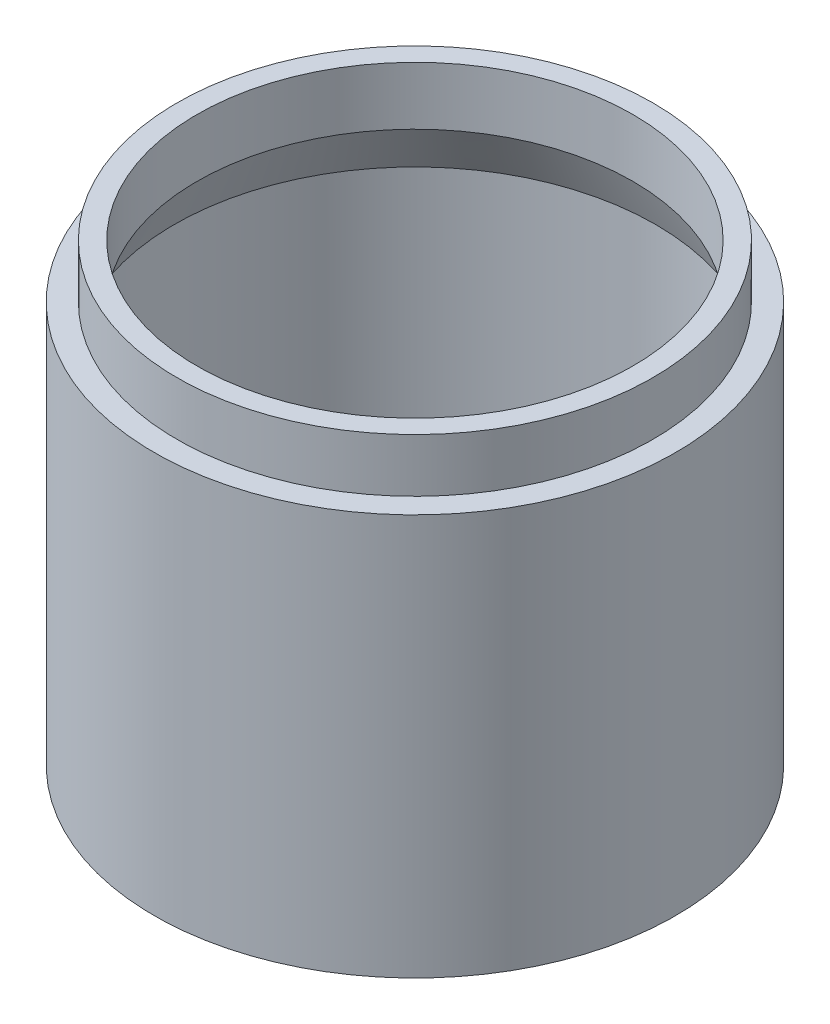
SolidWorks part; units mm, degrees
ref_plane "Front Plane" through (0, 0, 0) normal (0, 0, 1) x (1, 0, 0)
ref_plane "Top Plane" through (0, 0, 0) normal (0, 1, 0) x (1, 0, 0)
ref_plane "Right Plane" through (0, 0, 0) normal (1, 0, 0) x (0, 0, -1)
sketch "Sketch1" plane through (0, 0, 0) normal (1, 0, 0) x (0, 0, -1)
  line L0 (0, 0) -> (0, 323.85) construction
  line L1 (-51.054, 0) -> (-49.53, 0) construction
  line L2 (-51.054, 1000) -> (-51.054, 0) construction
  line L8 (0, 323.85) -> (0, 312.9504) construction
  line L9 (-41.743, 139.7) -> (-36.663, 139.7) construction
  line L10 (-36.663, 139.7) -> (-36.663, 131.6014) construction
  line L11 (-36.663, 131.6014) -> (-40.2294, 125.4241) construction
  line L13 (-25.3669, 0) -> (-49.53, 0) construction
  line L14 (-25.3669, 0) -> (-45.72, 0) construction
  line L15 (-47.7468, 3.302) -> (-44.961, 3.302) construction
  line L16 (-44.961, 3.302) -> (-65.4004, -58.5389) construction
  line L17 (-49.53, 0) -> (-68.5356, -57.5027) construction
  line L18 (-45.72, 0) -> (-45.72, 10.16) construction
  line L19 (-45.72, 10.16) -> (-47.6935, 11.0803) construction
  line L20 (-49.53, 0) -> (-49.53, -76.2)
  line L21 (-49.53, -76.2) -> (-45.72, -76.2)
  line L22 (-45.72, -76.2) -> (-45.72, -10.1046)
  line L23 (-45.72, -10.1046) -> (-41.402, -0.8447)
  line L24 (-41.402, -0.8447) -> (-41.402, 10.16)
  line L25 (-41.402, 10.16) -> (-45.212, 10.16)
  line L26 (-45.212, 10.16) -> (-45.212, 0)
  line L27 (-45.212, 0) -> (-49.53, 0)
  arc A2 (-51.054, 0) -> (-41.743, 139.7) centre (1001.6092, 0) cw construction
  arc A3 (-47.6935, 11.0803) -> (-40.2294, 125.4241) centre (1001.6092, 0) cw construction
  arc A4 (-47.7468, 3.302) -> (3.1419, 322.8341) centre (1001.6092, 0) cw construction
  arc A5 (-41.743, 139.7) -> (0, 323.85) centre (1001.6092, 0) cw construction
  arc A6 (-51.054, 0) -> (0, 323.85) centre (1001.6092, 0) cw construction
  arc A7 (-40.2294, 125.4241) -> (0, 312.9504) centre (1001.6092, 0) cw construction
  dimension "D6" = 139.7
  dimension "D1" = 323.85
  dimension "D2" = 5.334
  dimension "D3" = 51.054
  dimension "D4" = 10.16
  dimension "D5" = 3.302
  dimension "D7" = 5.08
  dimension "D8" = 8.0986
  dimension "D9" = 150
  dimension "D10" = 115
  dimension "D11" = 76.2
  dimension "D12" = 3.81
  dimension "D13" = 0.508
  dimension "D14" = 25
  dimension "D15" = 3.81
  dimension "D16" = 3.81
  dimension "D17" = 49.53
revolve "Revolve1" add sketch "Sketch1" angle 360 about L0
sketch "Sketch2" plane through (0, 0, 0) normal (1, 0, 0) x (0, 0, -1)
  line L0 (-45.72, -76.2) -> (45.72, -76.2) construction
  line L1 (4.445, -73.66) -> (-4.445, -73.66) construction
  line L2 (4.445, -73.66) -> (4.445, -76.2)
  line L3 (4.445, -76.2) -> (-4.445, -76.2)
  line L4 (-4.445, -73.66) -> (-4.445, -76.2)
  line L5 (4.445, -73.66) -> (-4.445, -76.2) construction
  line L6 (4.445, -76.2) -> (-4.445, -73.66) construction
  arc A0 (-4.445, -73.66) -> (4.445, -73.66) centre (0, -73.66) cw
  point P0 (0, -74.93)
  dimension "D1" = 8.89
  dimension "D2" = 2.54
extrude "Boss-Extrude1" add sketch "Sketch2" along normal up to next and the other way up to next
sketch "Sketch3" plane through (0, -76.2, 0) normal (0, -1, 0) x (1, 0, 0)
  circle A0 centre (0, 0) radius 45.72
extrude "Extrude-Thin1" add sketch "Sketch3" against normal blind 2.54 thin thin type one direction reverse wall 19.05
